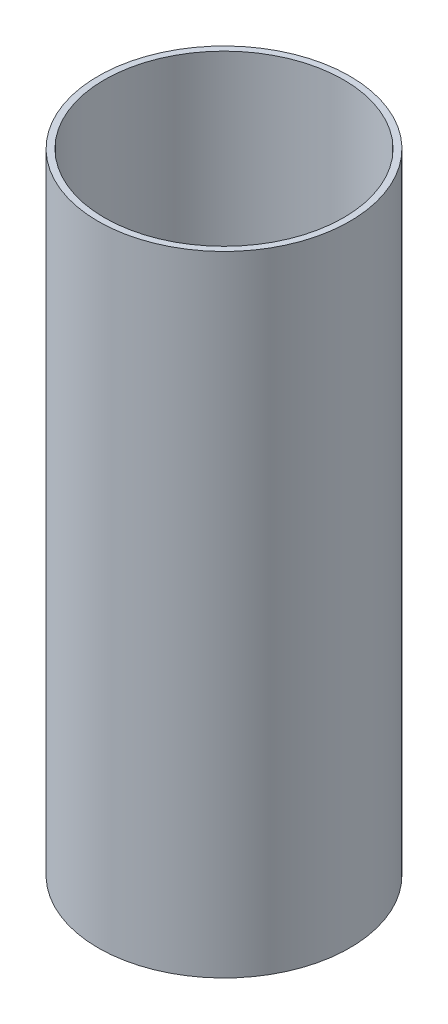
SolidWorks part; units mm, degrees
ref_plane "Front Plane" through (0, 0, 0) normal (0, 0, 1) x (1, 0, 0)
ref_plane "Top Plane" through (0, 0, 0) normal (0, 1, 0) x (1, 0, 0)
ref_plane "Right Plane" through (0, 0, 0) normal (1, 0, 0) x (0, 0, -1)
sketch "Sketch1" plane through (0, 0, 0) normal (0, 1, 0) x (1, 0, 0)
  circle A0 centre (0, 0) radius 38
  circle A1 centre (0, 0) radius 40
  dimension "D1" = 80
  dimension "D2" = 2
extrude "Boss-Extrude1" add sketch "Sketch1" along normal blind 200
